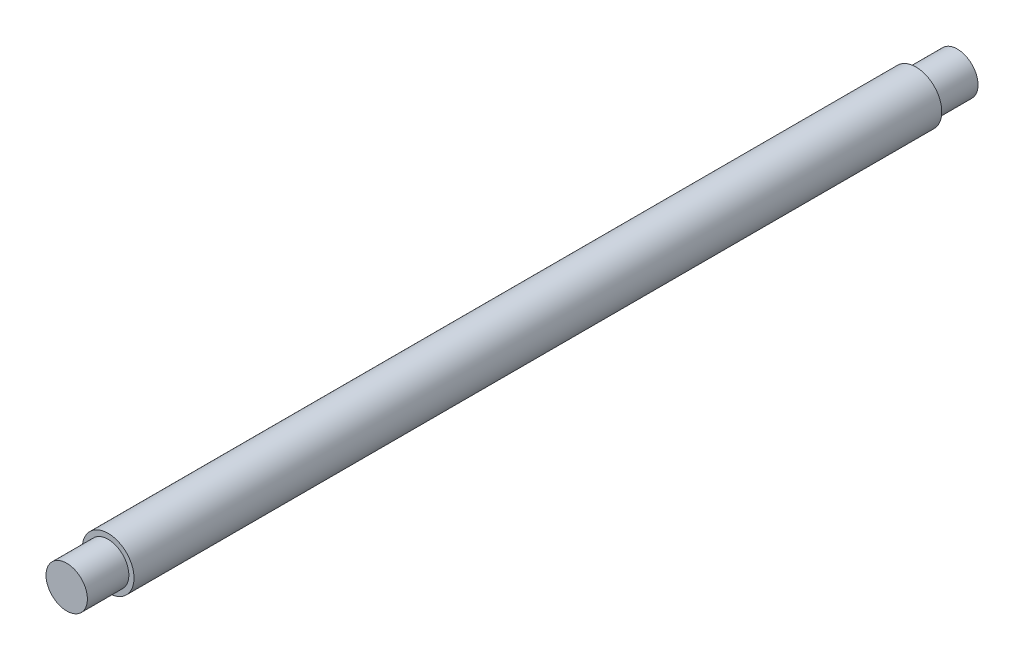
SolidWorks part; units mm, degrees
ref_plane "Front Plane" through (0, 0, 0) normal (0, 0, 1) x (1, 0, 0)
ref_plane "Top Plane" through (0, 0, 0) normal (0, 1, 0) x (1, 0, 0)
ref_plane "Right Plane" through (0, 0, 0) normal (1, 0, 0) x (0, 0, -1)
sketch "Sketch1" plane through (0, 0, 0) normal (0, 0, 1) x (1, 0, 0)
  circle A0 centre (0, 0) radius 5
  dimension "D1" = 10
extrude "Boss-Extrude1" add sketch "Sketch1" along normal blind 172
sketch "Sketch2" plane through (0, 0, 0) normal (0, 0, -1) x (-1, 0, 0)
  circle A0 centre (0, 0) radius 4
  circle A1 centre (0, 0) radius 5
  dimension "D1" = 8
extrude "Cut-Extrude1" cut sketch "Sketch2" against normal blind 8
ref_plane "Plane1" through (0, 0, 86) normal (0, 0, 1) x (1, 0, 0)
mirror "Mirror1" about plane through (0, 0, 86) normal (0, 0, 1) of "Cut-Extrude1"
